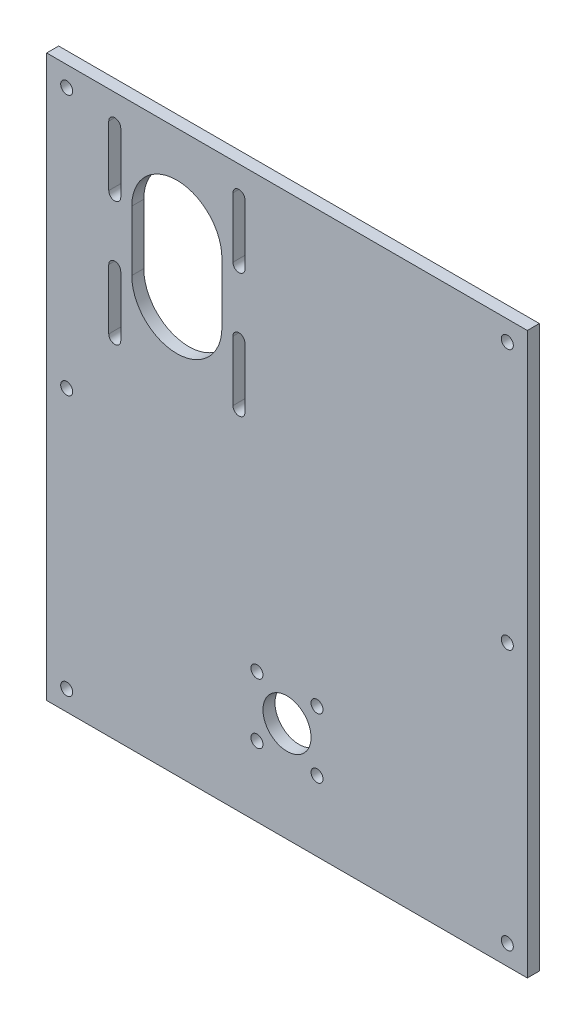
SolidWorks part; units mm, degrees
ref_plane "Plan de face" through (0, 0, 0) normal (0, 0, 1) x (1, 0, 0)
ref_plane "Plan de dessus" through (0, 0, 0) normal (0, 1, 0) x (1, 0, 0)
ref_plane "Plan de droite" through (0, 0, 0) normal (1, 0, 0) x (0, 0, -1)
sketch "Esquisse1" plane through (0, 0, 0) normal (0, 0, 1) x (1, 0, 0)
  line L0 (-27.5, 37.5) -> (-27.5, 52.5) construction
  line L1 (60, -75) -> (-60, -75)
  line L2 (60, -75) -> (60, 75)
  line L3 (60, 75) -> (-60, 75)
  line L4 (-60, -75) -> (-60, 75)
  line L5 (60, -75) -> (-60, 75) construction
  line L6 (60, 75) -> (-60, -75) construction
  line L9 (60, -65) -> (50, -65)
  line L10 (50, -75) -> (50, -65)
  line L13 (-60, -65) -> (-50, -65)
  line L14 (-50, -75) -> (-50, -65)
  line L15 (-38.75, 37.5) -> (-38.75, 52.5)
  line L16 (-16.25, 37.5) -> (-16.25, 52.5)
  line L17 (-43, 53) -> (-43, 68) construction
  line L18 (-44.5, 53) -> (-44.5, 68)
  line L19 (-41.5, 53) -> (-41.5, 68)
  line L20 (-43, 22) -> (-43, 37) construction
  line L21 (-44.5, 22) -> (-44.5, 37)
  line L22 (-41.5, 22) -> (-41.5, 37)
  line L24 (-27.5, 63.75) -> (-27.5, 26.25) construction
  line L27 (-12, 22) -> (-12, 37) construction
  line L30 (-10.5, 22) -> (-10.5, 37)
  line L31 (-13.5, 22) -> (-13.5, 37)
  line L32 (-12, 53) -> (-12, 68) construction
  line L33 (-10.5, 53) -> (-10.5, 68)
  line L34 (-13.5, 53) -> (-13.5, 68)
  arc A0 (-38.75, 37.5) -> (-16.25, 37.5) centre (-27.5, 37.5) ccw
  arc A1 (-16.25, 52.5) -> (-38.75, 52.5) centre (-27.5, 52.5) ccw
  arc A2 (-44.5, 53) -> (-41.5, 53) centre (-43, 53) ccw
  arc A3 (-41.5, 68) -> (-44.5, 68) centre (-43, 68) ccw
  arc A4 (-44.5, 22) -> (-41.5, 22) centre (-43, 22) ccw
  arc A5 (-41.5, 37) -> (-44.5, 37) centre (-43, 37) ccw
  arc A10 (-10.5, 22) -> (-13.5, 22) centre (-12, 22) cw
  arc A11 (-13.5, 37) -> (-10.5, 37) centre (-12, 37) cw
  arc A12 (-10.5, 53) -> (-13.5, 53) centre (-12, 53) cw
  arc A13 (-13.5, 68) -> (-10.5, 68) centre (-12, 68) cw
  point P0 (0, 0)
  point P14 (-27.5, 45)
  point P21 (-43, 60.5)
  point P28 (-43, 29.5)
  point P37 (-12, 29.5)
  point P44 (-12, 60.5)
  dimension "D1" = 10
  dimension "D2" = 10
  dimension "D3" = 150
  dimension "D4" = 120
  dimension "D5" = 32.5
  dimension "D6" = 15.5
  dimension "D7" = 22.5
  dimension "D8" = 3
  dimension "D9" = 15.5
  dimension "D10" = 15
  dimension "D11" = 3
  dimension "D12" = 31
extrude "Boss.-Extru.1" add sketch "Esquisse1" along normal blind 3 contours L14 L1 L10 L9 L2 L3 L4 L13 A5 L22 A4 L21 A3 L19 A2 L18 A1 L16 A0 L15 L31 A11 L30 A10 L34 A13 L33 A12
sketch "Esquisse2" plane through (0, 0, 3) normal (0, 0, 1) x (1, 0, 0)
  line L0 (-55, 75) -> (-55, -65) construction
  line L1 (60, 75) -> (-60, 75) construction
  line L2 (60, -65) -> (50, -65) construction
  line L3 (50, -70) -> (-50, -70) construction
  line L4 (50, -75) -> (50, -65) construction
  line L5 (-50, -75) -> (-50, -65) construction
  line L6 (0, 75) -> (0, -75) construction
  line L7 (50, -75) -> (-50, -75) construction
  circle A0 centre (45, -70) radius 1.5
  circle A3 centre (-55, -60) radius 1.5
  circle A4 centre (-55, 5) radius 1.5
  circle A5 centre (-55, 70) radius 1.5
  circle A9 centre (22.5, -70) radius 1.5
  circle A10 centre (0, -70) radius 1.5
  circle A11 centre (-22.5, -70) radius 1.5
  circle A12 centre (-45, -70) radius 1.5
  circle A13 centre (55, -60) radius 1.5
  circle A14 centre (55, 5) radius 1.5
  circle A15 centre (55, 70) radius 1.5
  dimension "D2" = 3
  dimension "D6" = 3
  dimension "D1" = 5
  dimension "D3" = 5
  dimension "D5" = 5
  dimension "D7" = 5
  dimension "D4" = 5
  dimension "D8" = 3
extrude "Enlèv. mat.-Extru.2" cut sketch "Esquisse2" against normal blind 3
sketch "Esquisse3" plane through (0, 0, 3) normal (0, 0, 1) x (1, 0, 0)
  line L3 (50, -75) -> (-50, -75) construction
  line L4 (0, 75) -> (0, -75) construction
  line L5 (60, 75) -> (-60, 75) construction
  line L6 (-7.5, -32.5) -> (7.5, -32.5) construction
  line L7 (7.5, -52.5) -> (-7.5, -52.5) construction
  line L8 (12.5, -47.5) -> (12.5, -32.5) construction
  line L9 (7.5, -27.5) -> (-7.5, -27.5) construction
  line L10 (-12.5, -47.5) -> (-12.5, -32.5) construction
  line L11 (12.5, -52.5) -> (-12.5, -27.5) construction
  line L12 (12.5, -27.5) -> (-12.5, -52.5) construction
  line L13 (-7.5, -32.5) -> (-7.5, -47.5) construction
  circle A0 centre (0, -40) radius 6
  arc A2 (-7.5, -52.5) -> (-12.5, -47.5) centre (-7.5, -47.5) cw construction
  arc A3 (7.5, -52.5) -> (12.5, -47.5) centre (7.5, -47.5) ccw construction
  arc A4 (12.5, -32.5) -> (7.5, -27.5) centre (7.5, -32.5) ccw construction
  arc A5 (-7.5, -27.5) -> (-12.5, -32.5) centre (-7.5, -32.5) ccw construction
  circle A6 centre (-7.5, -32.5) radius 1.5
  circle A7 centre (7.5, -32.5) radius 1.5
  circle A8 centre (7.5, -47.5) radius 1.5
  circle A9 centre (-7.5, -47.5) radius 1.5
  dimension "D1" = 12
  dimension "D2" = 35
  dimension "D3" = 25
  dimension "D4" = 5
  dimension "D5" = 3
  dimension "D6" = 2
  dimension "D7" = 2
extrude "Enlèv. mat.-Extru.3" cut sketch "Esquisse3" against normal blind 10
sketch "Esquisse4" plane through (0, 0, 3) normal (0, 0, 1) x (1, 0, 0)
  line L0 (-50, -65) -> (50, -65)
  line L1 (50, -65) -> (50, -76.4572)
  line L2 (50, -76.4572) -> (-50, -76.4572)
  line L3 (-50, -76.4572) -> (-50, -65)
extrude "Enlèv. mat.-Extru.4" cut sketch "Esquisse4" against normal blind 10
